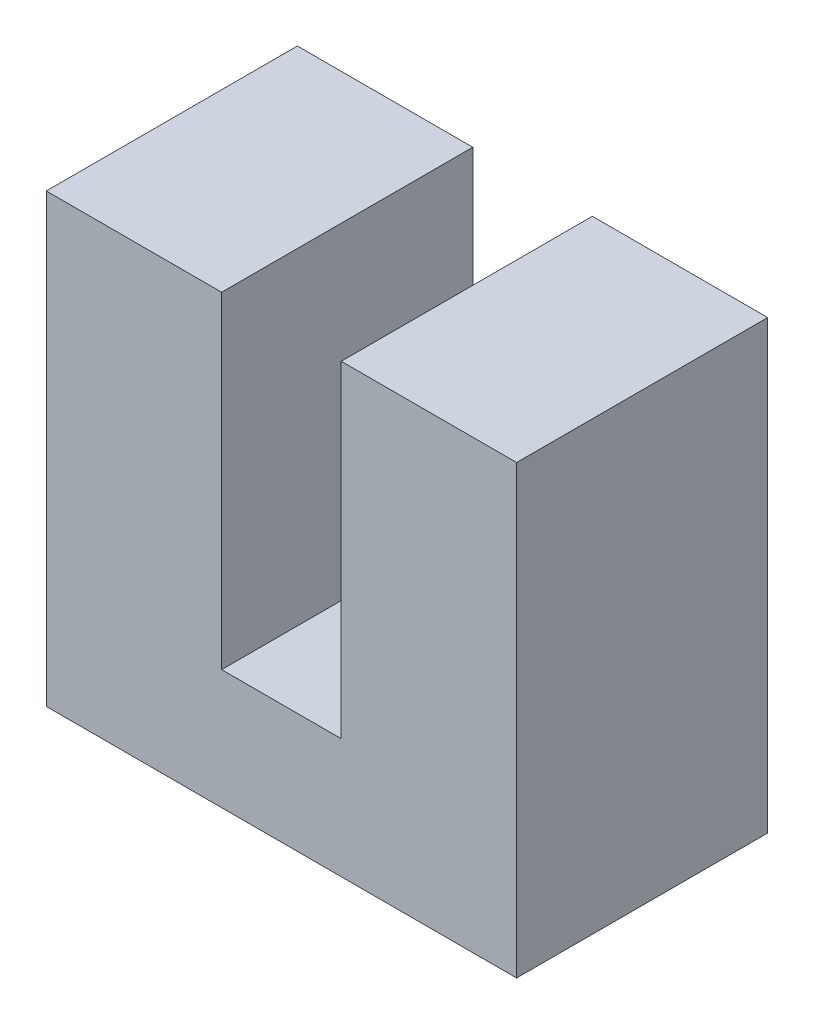
SolidWorks part; units mm, degrees
ref_plane "Front Plane" through (0, 0, 0) normal (0, 0, 1) x (1, 0, 0)
ref_plane "Top Plane" through (0, 0, 0) normal (0, 1, 0) x (1, 0, 0)
ref_plane "Right Plane" through (0, 0, 0) normal (1, 0, 0) x (0, 0, -1)
sketch "Sketch1" plane through (0, 0, 0) normal (0, 0, 1) x (1, 0, 0)
  line L0 (0, 0) -> (11.8, 0)
  line L1 (11.8, 0) -> (11.8, 11.2)
  line L2 (11.8, 11.2) -> (7.4, 11.2)
  line L3 (7.4, 11.2) -> (7.4, 3)
  line L4 (7.4, 3) -> (4.4, 3)
  line L5 (4.4, 3) -> (4.4, 11.2)
  line L6 (4.4, 11.2) -> (0, 11.2)
  line L7 (0, 11.2) -> (0, 0)
  dimension "D1" = 11.2
  dimension "D2" = 4.4
  dimension "D3" = 3
  dimension "D4" = 3
extrude "Boss-Extrude1" add sketch "Sketch1" along normal blind 6.3
